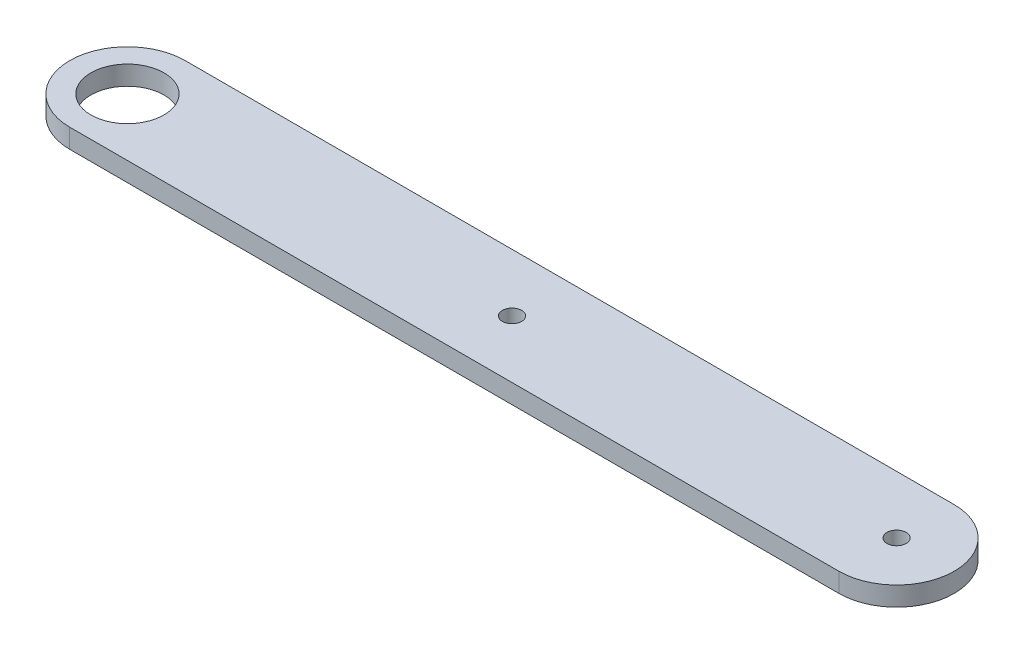
SolidWorks part; units mm, degrees
ref_plane "前视基准面" through (0, 0, 0) normal (0, 0, 1) x (1, 0, 0)
ref_plane "上视基准面" through (0, 0, 0) normal (0, 1, 0) x (1, 0, 0)
ref_plane "右视基准面" through (0, 0, 0) normal (1, 0, 0) x (0, 0, -1)
other "Configuration Table"
sketch "草图1" plane through (0, 0, 0) normal (0, 1, 0) x (1, 0, 0)
  line L0 (0, 0) -> (200, 0) construction
  line L1 (0, 15) -> (200, 15)
  line L2 (0, -15) -> (200, -15)
  arc A0 (0, 15) -> (0, -15) centre (0, 0) ccw
  arc A1 (200, -15) -> (200, 15) centre (200, 0) ccw
  circle A2 centre (200, 0) radius 2.5
  circle A3 centre (100, 0) radius 2.5
  circle A4 centre (0, 0) radius 9.5
  point P3 (100, 0)
  dimension "D2" = 15
  dimension "D3" = 5
  dimension "D4" = 19
  dimension "D5" = 5
  dimension "D1" = 200
extrude "凸台-拉伸1" add sketch "草图1" along normal blind 5
